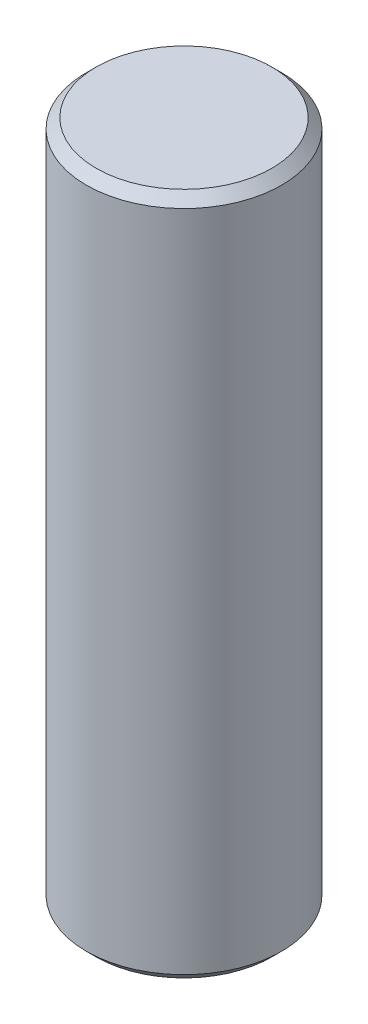
SolidWorks part; units mm, degrees
ref_plane "前视基准面" through (0, 0, 0) normal (0, 0, 1) x (1, 0, 0)
ref_plane "上视基准面" through (0, 0, 0) normal (0, 1, 0) x (1, 0, 0)
ref_plane "右视基准面" through (0, 0, 0) normal (1, 0, 0) x (0, 0, -1)
other "Configuration Table"
sketch "草图1" plane through (0, 0, 0) normal (0, 1, 0) x (1, 0, 0)
  circle A0 centre (0, 0) radius 2
  dimension "D1" = 4
extrude "凸台-拉伸1" add sketch "草图1" along normal blind 14
chamfer "倒角1" distance 0.2 angle 45 2 edges at (0, 0, 2) (0, 14, 2)
